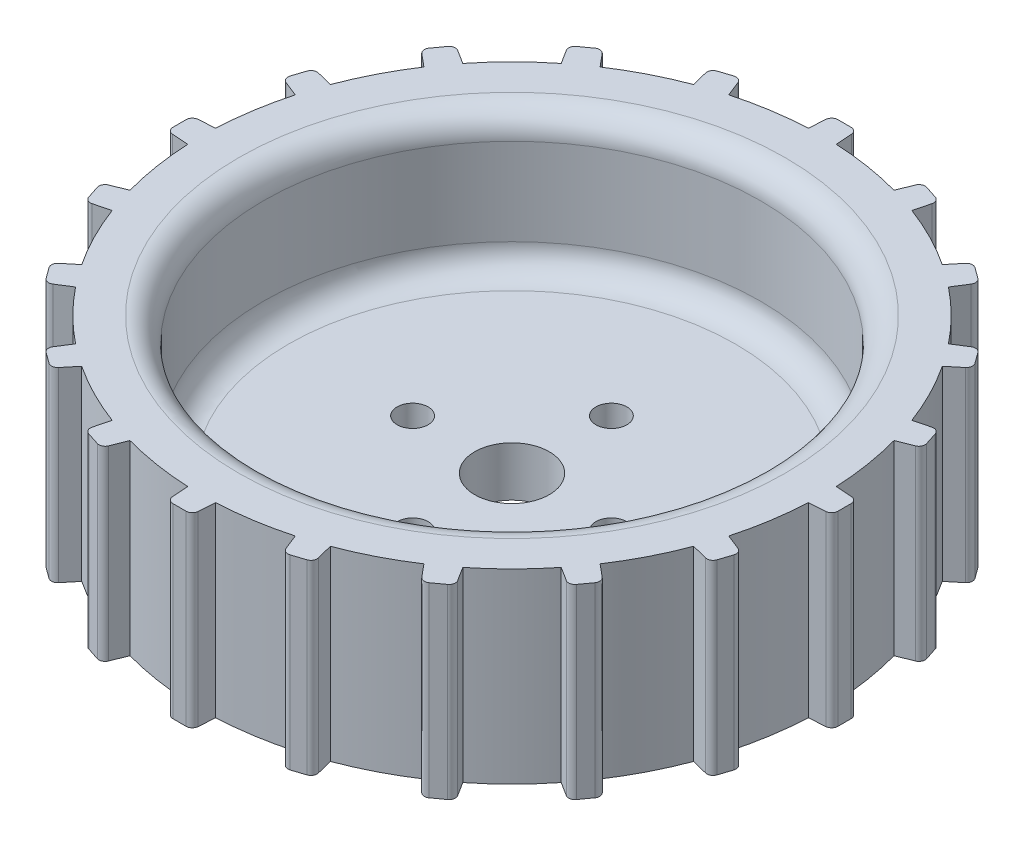
SolidWorks part; units mm, degrees
ref_plane "Front" through (0, 0, 0) normal (0, 0, 1) x (1, 0, 0)
ref_plane "Top" through (0, 0, 0) normal (0, 1, 0) x (1, 0, 0)
ref_plane "Right" through (0, 0, 0) normal (1, 0, 0) x (0, 0, -1)
sketch "Sketch1" plane through (0, 0, 0) normal (0, 1, 0) x (1, 0, 0)
  line L0 (0, 0) -> (0, 8) construction
  circle A0 centre (0, 0) radius 25
  circle A1 centre (0, 0) radius 3
  circle A2 centre (0, 8) radius 1.25
  circle A3 centre (8, 0) radius 1.25
  circle A4 centre (0, -8) radius 1.25
  circle A5 centre (-8, 0) radius 1.25
  point P15 (0, 0)
  dimension "D1" = 50
  dimension "D2" = 6
  dimension "D4" = 2.5
  dimension "D3" = 8
  dimension "D5" = 4
extrude "Boss-Extrude1" add sketch "Sketch1" along normal blind 15
sketch "Sketch2" plane through (0, 15, 0) normal (0, 1, 0) x (1, 0, 0)
  circle A0 centre (0, 0) radius 20
  dimension "D1" = 40
extrude "Cut-Extrude1" cut sketch "Sketch2" against normal blind 11
fillet "Fillet1" radius 2 2 edges at (0, 4, 20) (0, 15, 20)
sketch "Sketch3" plane through (0, 0, 0) normal (0, -1, 0) x (1, 0, 0)
  line L0 (0, 0) -> (0, -27.8181) construction
  line L1 (1.1759, -24.0941) -> (1.0341, -26.2974)
  line L2 (0.5352, -26.7653) -> (-0.5352, -26.7653)
  line L3 (1.1759, -24.0941) -> (-1.1759, -24.0941)
  line L4 (-1.1759, -24.0941) -> (-1.0341, -26.2974)
  arc A0 (1.0341, -26.2974) -> (0.5352, -26.7653) centre (0.5352, -26.2653) cw
  arc A1 (-1.0341, -26.2974) -> (-0.5352, -26.7653) centre (-0.5352, -26.2653) ccw
  point P8 (0, -26.7653)
  point P9 (0, -24.0941)
  point P10 (0, -26.7653)
  point P12 (0.5352, -26.7653)
  point P16 (0, -24.0941)
  dimension "D1" = 0.5
extrude "Boss-Extrude2" add sketch "Sketch3" against normal up to surface (15 mm away) up to face at (0, 15, 22)
pattern_circular "CirPattern1" count 20 over 360 about axis through (0, 0, 0) along (0, 1, 0) of "Boss-Extrude2"
